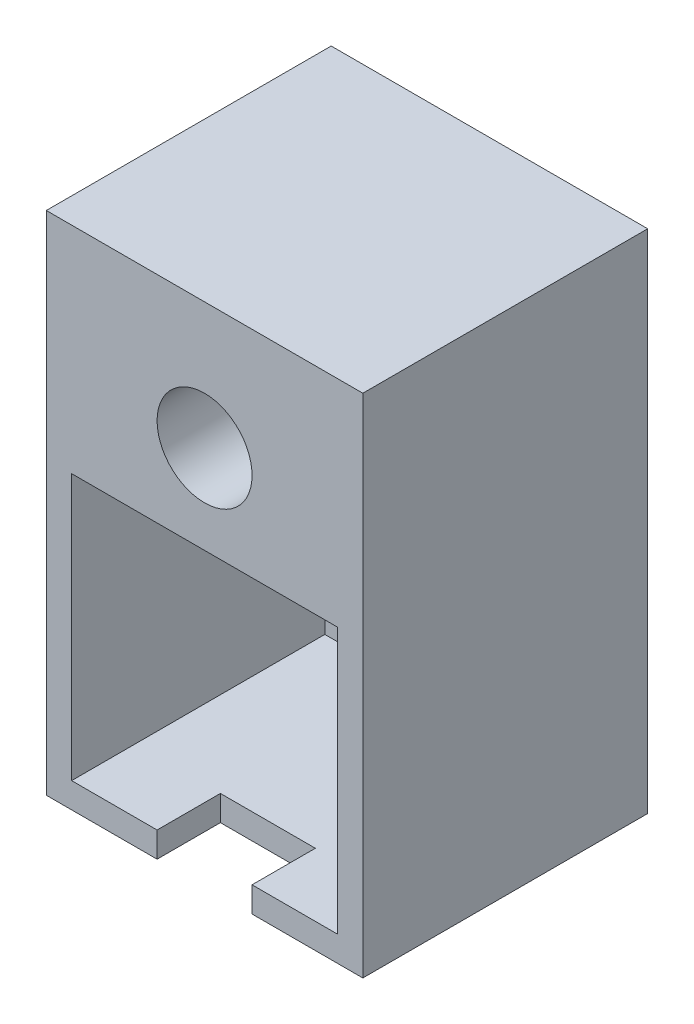
SolidWorks part; units mm, degrees
ref_plane "Front Plane" through (0, 0, 0) normal (0, 0, 1) x (1, 0, 0)
ref_plane "Top Plane" through (0, 0, 0) normal (0, 1, 0) x (1, 0, 0)
ref_plane "Right Plane" through (0, 0, 0) normal (1, 0, 0) x (0, 0, -1)
sketch "Sketch1" plane through (0, 0, 0) normal (0, 0, 1) x (1, 0, 0)
  line L1 (25, -40) -> (-25, -40)
  line L2 (25, -40) -> (25, 40)
  line L3 (25, 40) -> (-25, 40)
  line L4 (-25, -40) -> (-25, 40)
  line L5 (25, -40) -> (-25, 40) construction
  line L6 (25, 40) -> (-25, -40) construction
  point P0 (0, 0)
  dimension "D1" = 80
  dimension "D2" = 50
extrude "Boss-Extrude1" add sketch "Sketch1" along normal blind 45
sketch "Sketch2" plane through (0, 0, 0) normal (0, 0, -1) x (-1, 0, 0)
  line L0 (-25, 40) -> (25, 40) construction
  line L1 (25, 40) -> (0, 40) construction
  line L2 (0, 40) -> (0, 20) construction
  circle A0 centre (0, 20) radius 2.5
  dimension "D2" = 5
  dimension "D1" = 20
sketch "Sketch5" plane through (0, 0, 45) normal (0, 0, 1) x (1, 0, 0)
  line L0 (25, -40) -> (-25, -40) construction
  line L1 (0, -40) -> (0, -15) construction
  line L3 (21, 6) -> (-21, 6)
  line L4 (21, 6) -> (21, -36)
  line L5 (21, -36) -> (-21, -36)
  line L6 (-21, 6) -> (-21, -36)
  line L7 (21, 6) -> (-21, -36) construction
  line L8 (21, -36) -> (-21, 6) construction
  dimension "D1" = 25
  dimension "D2" = 42
  dimension "D3" = 42
extrude "Cut-Extrude1" cut sketch "Sketch5" against normal blind 40
sketch "Sketch6" plane through (0, 0, 5) normal (0, 0, 1) x (1, 0, 0)
  line L0 (0, 6) -> (0, -36) construction
  line L1 (21, 6) -> (-21, 6) construction
  line L2 (-21, -36) -> (21, -36) construction
  line L3 (0, -15) -> (14.2241, -15) construction
  circle A0 centre (15.5, -30.5) radius 1.5
  circle A1 centre (15.5, 0.5) radius 1.5
  circle A2 centre (-15.5, -30.5) radius 1.5
  circle A3 centre (-15.5, 0.5) radius 1.5
  dimension "D1" = 3
  dimension "D2" = 15.5
  dimension "D3" = 31
extrude "Cut-Extrude2" cut sketch "Sketch6" against normal blind 40
sketch "Sketch7" plane through (0, 0, 45) normal (0, 0, 1) x (1, 0, 0)
  line L0 (-25, -40) -> (25, -40) construction
  line L1 (7.5, -60.8448) -> (-7.5, -60.8448)
  line L2 (7.5, -60.8448) -> (7.5, -19.1552)
  line L3 (7.5, -19.1552) -> (-7.5, -19.1552)
  line L4 (-7.5, -60.8448) -> (-7.5, -19.1552)
  line L5 (7.5, -60.8448) -> (-7.5, -19.1552) construction
  line L6 (7.5, -19.1552) -> (-7.5, -60.8448) construction
  point P0 (0, -40)
  dimension "D1" = 15
extrude "Cut-Extrude3" cut sketch "Sketch7" against normal blind 10
sketch "Sketch8" plane through (0, 0, 5) normal (0, 0, 1) x (1, 0, 0)
  circle A0 centre (0, -15) radius 11
  dimension "D1" = 22
extrude "Cut-Extrude4" cut sketch "Sketch8" against normal blind 2
sketch "Sketch9" plane through (0, 0, 3) normal (0, 0, 1) x (1, 0, 0)
  circle A0 centre (0, -15) radius 2
  dimension "D1" = 4
extrude "Cut-Extrude5" cut sketch "Sketch9" against normal blind 10
extrude "Cut-Extrude6" cut sketch "Sketch2" against normal blind 10
sketch "Sketch10" plane through (0, 0, 0) normal (0, 0, -1) x (-1, 0, 0)
  circle A0 centre (0, 20) radius 7.5
  dimension "D1" = 15
extrude "Cut-Extrude7" cut sketch "Sketch10" against normal blind 48
